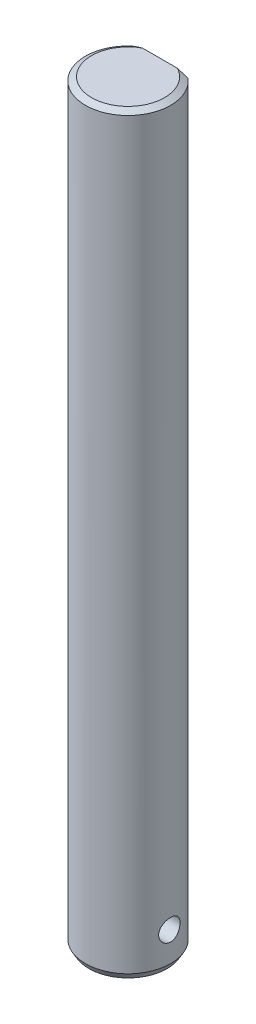
SolidWorks part; units mm, degrees
ref_plane "Front Plane" through (0, 0, 0) normal (0, 0, 1) x (1, 0, 0)
ref_plane "Top Plane" through (0, 0, 0) normal (0, 1, 0) x (1, 0, 0)
ref_plane "Right Plane" through (0, 0, 0) normal (1, 0, 0) x (0, 0, -1)
sketch "Sketch1" plane through (0, 0, 0) normal (0, 1, 0) x (1, 0, 0)
  circle A0 centre (0, 0) radius 6
  dimension "D1" = 12
extrude "Boss-Extrude1" add sketch "Sketch1" along normal blind 106
sketch "Sketch2" plane through (0, 106, 0) normal (0, 1, 0) x (1, 0, 0)
  line L1 (-17.6992, 14.7161) -> (13.74, 14.7161)
  line L2 (-17.6992, 14.7161) -> (-17.6992, 4.5)
  line L3 (-17.6992, 4.5) -> (13.74, 4.5)
  line L4 (13.74, 14.7161) -> (13.74, 4.5)
  line L5 (-17.6992, 14.7161) -> (13.74, 4.5) construction
  line L6 (-17.6992, 4.5) -> (13.74, 14.7161) construction
  point P0 (-1.9796, 9.6081)
  dimension "D1" = 4.5
extrude "Cut-Extrude1" cut sketch "Sketch2" against normal blind 10
sketch "Sketch4" plane through (0, 0, 0) normal (1, 0, 0) x (0, 0, -1)
  circle A0 centre (0, 5) radius 1.5
  point P2 (-0.3269, 0.892)
  dimension "D1" = 3
  dimension "D2" = 5
extrude "Cut-Extrude2" cut sketch "Sketch4" against normal mid plane 50
chamfer "Chamfer1" distance 0.5 angle 60 2 edges at (0, 106, 6) (0, 0, 6)
